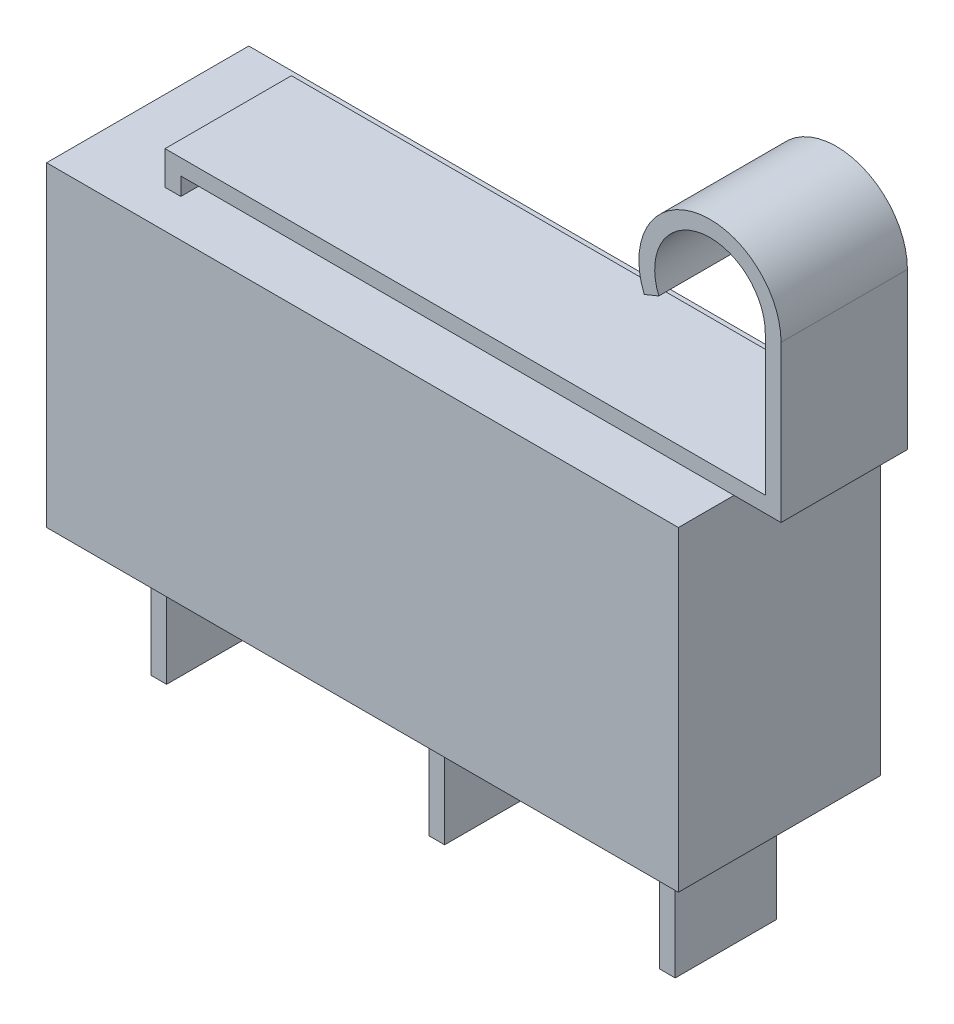
SolidWorks part; units mm, degrees
ref_plane "Спереди" through (0, 0, 0) normal (0, 0, 1) x (1, 0, 0)
ref_plane "Сверху" through (0, 0, 0) normal (0, 1, 0) x (1, 0, 0)
ref_plane "Справа" through (0, 0, 0) normal (1, 0, 0) x (0, 0, -1)
sketch "Эскиз1" plane through (0, 0, 0) normal (0, 0, 1) x (1, 0, 0)
  line L1 (-20, 0) -> (0, 0)
  line L2 (-20, 0) -> (-20, 10)
  line L3 (-20, 10) -> (0, 10)
  line L4 (0, 0) -> (0, 10)
  point P4 (0, 0)
  dimension "D1" = 20
  dimension "D2" = 10
extrude "Бобышка-Вытянуть1" add sketch "Эскиз1" along normal mid plane 6.4
sketch "Эскиз2" plane through (0, 0, 0) normal (0, -1, 0) x (1, 0, 0)
  line L0 (-18.05, 1.6) -> (-18.05, -1.6)
  line L1 (-9.25, 1.6) -> (-9.25, -1.6)
  line L2 (-1.95, 1.6) -> (-1.95, -1.6)
  line L3 (0, 0) -> (-20, 0) construction
  line L4 (0, 3.2) -> (0, -3.2) construction
  line L5 (-20, 3.2) -> (-20, -3.2) construction
  line L6 (-18.05, -1.6) -> (-1.95, -1.6) construction
  line L7 (-10, -1.6) -> (-10, 0) construction
  point P12 (-18.05, 0)
  point P13 (-9.25, 0)
  point P14 (-1.95, 0)
  dimension "D1" = 3.2
  dimension "D2" = 8.8
  dimension "D3" = 7.3
extrude "Вытянуть-Тонкостенный1" add sketch "Эскиз2" along normal blind 4 thin thin type mid plane wall 0.5
sketch "Эскиз3" plane through (0, 0, 0) normal (0, 0, 1) x (1, 0, 0)
  line L0 (-17.2, 10) -> (-17.2, 10.8113)
  line L1 (0, 10) -> (-20, 10) construction
  line L2 (-17.2, 10.8113) -> (1.8, 10.8113)
  line L3 (1.8, 10.8113) -> (1.8, 15.5)
  line L4 (-0.2, 17.5) -> (2.0835, 17.5) construction
  arc A0 (1.8, 15.5) -> (-2.0511, 14.7428) centre (-0.2, 15.5) ccw
  point P8 (-20, 10)
  point P9 (-0.2, 17.5)
  point P13 (-2.1284, 14.6277)
  dimension "D4" = 2
  dimension "D1" = 2.8
  dimension "D2" = 17
  dimension "D3" = 17.5
extrude "Вытянуть-Тонкостенный2" add sketch "Эскиз3" along normal mid plane 4 thin thin type mid plane wall 0.5
